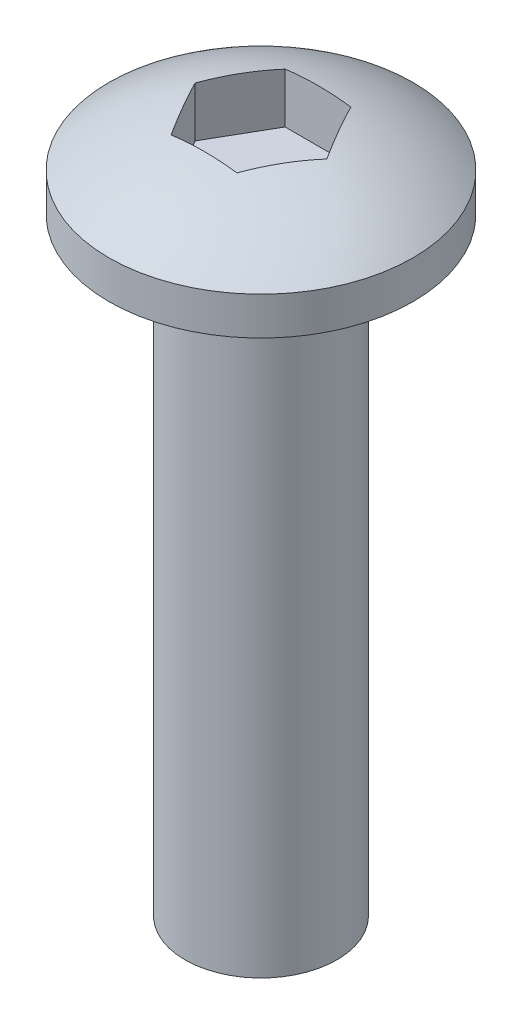
SolidWorks part; units mm, degrees
material "1.0570 (S355J2G3)"
ref_plane "Front Plane" through (0, 0, 0) normal (0, 0, 1) x (1, 0, 0)
ref_plane "Top Plane" through (0, 0, 0) normal (0, 1, 0) x (1, 0, 0)
ref_plane "Right Plane" through (0, 0, 0) normal (1, 0, 0) x (0, 0, -1)
sketch "Sketch1" plane through (0, 0, 0) normal (0, 1, 0) x (1, 0, 0)
  circle A0 centre (0, 0) radius 1
  dimension "D1" = 2
extrude "Boss-Extrude1" add sketch "Sketch1" along normal blind 8
sketch "Sketch2" plane through (0, 0, 0) normal (0, 0, 1) x (1, 0, 0)
  line L0 (0, 8) -> (-2, 8)
  line L1 (1, 8) -> (-1, 8) construction
  line L2 (0, 8) -> (0, 9.1751)
  line L3 (-2, 8) -> (-2, 8.5)
  arc A0 (0, 9.1751) -> (-2, 8.5) centre (0, 5.8751) ccw
  dimension "D2" = 3.3
  dimension "D1" = 0.5
  dimension "D3" = 2
revolve "Revolve2" add sketch "Sketch2" angle 360 about L2
sketch "Sketch3" plane through (0, 0, 0) normal (0, 1, 0) x (1, 0, 0)
  line L1 (0.433, -0.75) -> (0.866, 0)
  line L2 (0.866, 0) -> (0.433, 0.75)
  line L3 (0.433, 0.75) -> (-0.433, 0.75)
  line L4 (-0.433, 0.75) -> (-0.866, 0)
  line L5 (-0.866, 0) -> (-0.433, -0.75)
  line L6 (-0.433, -0.75) -> (0.433, -0.75)
  circle A0 centre (0, 0) radius 0.75 construction
  dimension "D1" = 1.5
extrude "Cut-Extrude1" cut sketch "Sketch3" against normal blind 1.1 from offset 9.5
